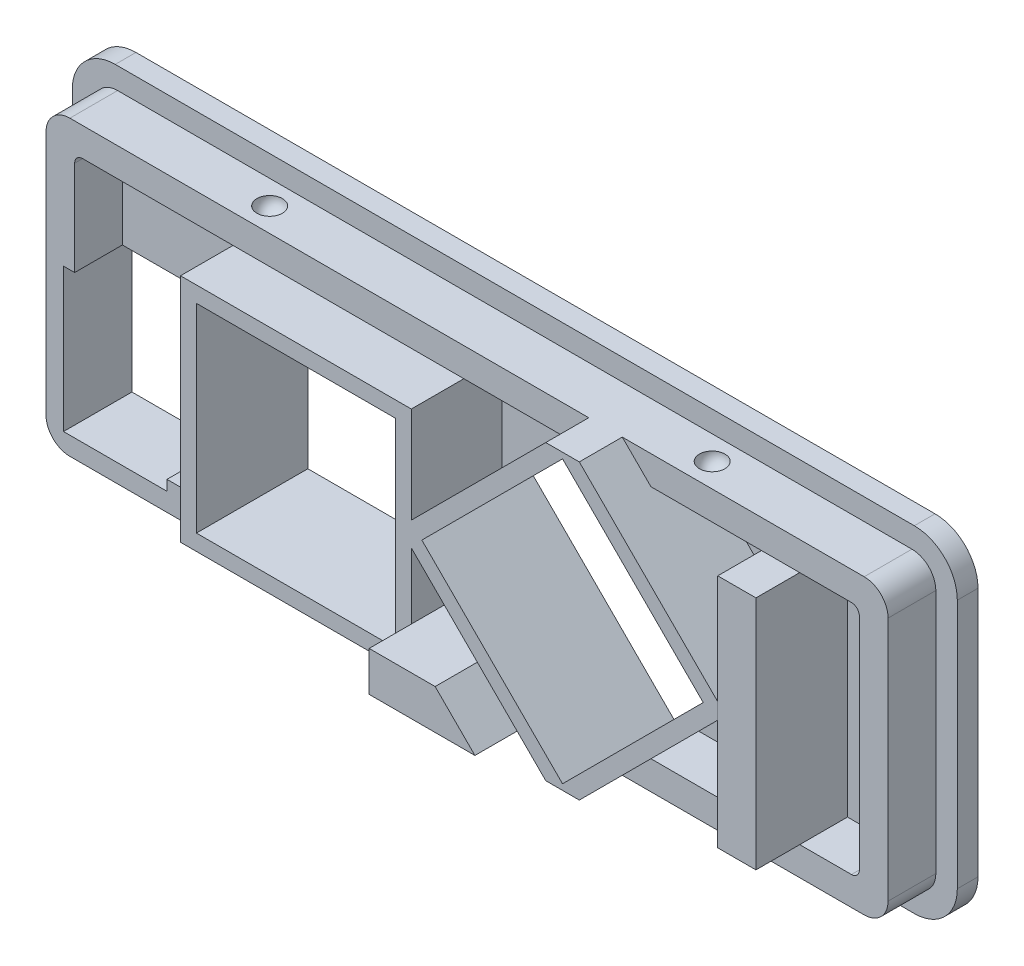
SolidWorks part; units mm, degrees
material "PLA"
ref_plane "Front Plane" through (0, 0, 0) normal (0, 0, 1) x (1, 0, 0)
ref_plane "Top Plane" through (0, 0, 0) normal (0, 1, 0) x (1, 0, 0)
ref_plane "Right Plane" through (0, 0, 0) normal (1, 0, 0) x (0, 0, -1)
sketch "Sketch1" plane through (0, 0, 0) normal (0, 0, 1) x (1, 0, 0)
  line L1 (2.7, 0) -> (52.9, 0)
  line L2 (0, 2.7) -> (0, 18.4)
  line L3 (2.7, 21.1) -> (52.9, 21.1)
  line L4 (55.6, 2.7) -> (55.6, 18.4)
  arc A0 (52.9, 0) -> (55.6, 2.7) centre (52.9, 2.7) ccw
  arc A1 (2.7, 0) -> (0, 2.7) centre (2.7, 2.7) cw
  arc A2 (0, 18.4) -> (2.7, 21.1) centre (2.7, 18.4) cw
  arc A3 (52.9, 21.1) -> (55.6, 18.4) centre (52.9, 18.4) cw
  point P9 (0, 0)
  dimension "D1" = 2.7
  dimension "D2" = 50.2
  dimension "D3" = 15.7
extrude "Boss-Extrude1" add sketch "Sketch1" along normal blind 1.3
sketch "Sketch4" plane through (0, 0, 1.3) normal (0, 0, 1) x (1, 0, 0)
  line L11 (54.25, 2.7) -> (54.25, 18.4)
  line L12 (52.9, 19.75) -> (2.7, 19.75)
  line L13 (1.35, 18.4) -> (1.35, 2.7)
  line L14 (2.7, 1.35) -> (52.9, 1.35)
  line L15 (54.25, 2.85) -> (54.25, 18.25)
  line L16 (52.75, 19.75) -> (2.85, 19.75)
  line L17 (1.35, 18.25) -> (1.35, 2.85)
  line L18 (2.85, 1.35) -> (52.75, 1.35)
  arc A4 (54.25, 18.25) -> (52.75, 19.75) centre (52.75, 18.25) ccw
  arc A5 (54.25, 2.85) -> (52.75, 1.35) centre (52.75, 2.85) cw
  arc A6 (1.35, 2.85) -> (2.85, 1.35) centre (2.85, 2.85) ccw
  arc A7 (2.85, 19.75) -> (1.35, 18.25) centre (2.85, 18.25) ccw
  arc A8 (52.9, 1.35) -> (54.25, 2.7) centre (52.9, 2.7) ccw
  arc A10 (54.25, 18.4) -> (52.9, 19.75) centre (52.9, 18.4) ccw
  arc A12 (2.7, 19.75) -> (1.35, 18.4) centre (2.7, 18.4) ccw
  arc A14 (1.35, 2.7) -> (2.7, 1.35) centre (2.7, 2.7) ccw
  dimension "D2" = 1.5
  dimension "D1" = 1.35
extrude "Boss-Extrude3" add sketch "Sketch4" along normal blind 3
sketch "Sketch5" plane through (0, 0, 4.3) normal (0, 0, 1) x (1, 0, 0)
  line L8 (52.45, 17.95) -> (3.15, 17.95)
  line L9 (3.15, 17.95) -> (3.15, 3.15)
  line L10 (3.15, 3.15) -> (52.45, 3.15)
  line L11 (52.45, 3.15) -> (52.45, 17.95)
  line L12 (51.95, 17.95) -> (3.65, 17.95)
  line L13 (3.15, 17.45) -> (3.15, 3.65)
  line L14 (3.65, 3.15) -> (51.95, 3.15)
  line L15 (52.45, 3.65) -> (52.45, 17.45)
  arc A4 (51.95, 3.15) -> (52.45, 3.65) centre (51.95, 3.65) ccw
  arc A5 (51.95, 17.95) -> (52.45, 17.45) centre (51.95, 17.45) cw
  arc A6 (3.65, 17.95) -> (3.15, 17.45) centre (3.65, 17.45) ccw
  arc A7 (3.15, 3.65) -> (3.65, 3.15) centre (3.65, 3.65) ccw
  dimension "D2" = 0.5
  dimension "D1" = 1.8
extrude "Cut-Extrude1" cut sketch "Sketch5" against normal blind 3
sketch "Sketch10" plane through (0, 19.75, 0) normal (0, 1, 0) x (1, 0, 0)
  line L0 (41.7, -2) -> (41.7, -3.6)
  line L1 (41.7, -3.6) -> (42.6713, -3.8888)
  line L3 (52.75, -1.3) -> (2.85, -1.3) construction
  line L4 (55.6, -1.3) -> (55.6, 0) construction
  arc A0 (41.7, -2) -> (41.7, -3.6) centre (41.7, -2.8) ccw
  dimension "D2" = 0.8
  dimension "D1" = 1.6
  dimension "D3" = 1.5
  dimension "D4" = 13.9
revolve "Cut-Revolve1" cut sketch "Sketch10" angle 360 about L0
ref_plane "Plane1" through (0, 10.55, 0) normal (0, -1, 0) x (-1, 0, 0)
mirror "Mirror1" about plane through (0, 10.55, 0) normal (0, -1, 0) of "Cut-Revolve1"
sketch "Sketch11" plane through (0, 0, 0) normal (0, 0, -1) x (-1, 0, 0)
  line L0 (0, 18.4) -> (0, 2.7) construction
  line L1 (-2.45, 2.5) -> (-8.95, 2.5)
  line L2 (-2.45, 2.5) -> (-2.45, 11.5)
  line L3 (-2.45, 11.5) -> (-8.95, 11.5)
  line L4 (-8.95, 2.5) -> (-8.95, 11.5)
  line L5 (-2.45, 2.5) -> (-8.95, 11.5) construction
  line L6 (-2.45, 11.5) -> (-8.95, 2.5) construction
  line L8 (-2.7, 0) -> (-52.9, 0) construction
  point P0 (-5.7, 7)
  dimension "D1" = 5.7
  dimension "D2" = 2.5
  dimension "D3" = 9
  dimension "D4" = 6.5
extrude "Cut-Extrude2" cut sketch "Sketch11" against normal blind 4.3
sketch "Sketch12" plane through (0, 0, 0) normal (0, 0, -1) x (-1, 0, 0)
  line L1 (-26, 16.35) -> (-13.5, 16.35)
  line L2 (-26, 16.35) -> (-26, 3.85)
  line L3 (-26, 3.85) -> (-13.5, 3.85)
  line L4 (-13.5, 16.35) -> (-13.5, 3.85)
  line L5 (-26, 16.35) -> (-13.5, 3.85) construction
  line L6 (-26, 3.85) -> (-13.5, 16.35) construction
  line L7 (-52.9, 21.1) -> (-2.7, 21.1) construction
  line L9 (0, 18.4) -> (0, 2.7) construction
  point P0 (-19.75, 10.1)
  dimension "D1" = 11
  dimension "D2" = 19.75
  dimension "D3" = 12.5
  dimension "D4" = 12.5
sketch "Sketch13" plane through (0, 0, 0) normal (0, 0, -1) x (-1, 0, 0)
  line L0 (-45.3388, 10.55) -> (-36.5, 1.7112)
  line L1 (-45.3388, 10.55) -> (-36.5, 19.3888)
  line L2 (-36.5, 1.7112) -> (-27.6612, 10.55)
  line L3 (-36.5, 19.3888) -> (-27.6612, 10.55)
  line L4 (-45.3388, 10.55) -> (-27.6612, 10.55) construction
  line L5 (-36.5, 1.7112) -> (-36.5, 19.3888) construction
  line L6 (-0.715, 10.55) -> (0.715, 10.55) construction
  line L7 (-52.9, 21.1) -> (-2.7, 21.1) construction
  line L10 (0, 18.4) -> (0, 2.7) construction
  point P1 (-36.5, 10.55)
  dimension "D1" = 0
  dimension "D2" = 10.55
  dimension "D3" = 12.5
  dimension "D5" = 36.5
extrude "Cut-Extrude4" cut sketch "Sketch12" against normal blind 1.3
sketch "Sketch17" plane through (0, 0, 0) normal (0, 0, -1) x (-1, 0, 0)
  line L8 (-13.5, 16.35) -> (-26, 16.35) construction
  line L9 (-27, 17.35) -> (-12.5, 17.35)
  line L10 (-27, 17.35) -> (-27, 2.85)
  line L11 (-27, 2.85) -> (-12.5, 2.85)
  line L12 (-12.5, 17.35) -> (-12.5, 2.85)
  line L13 (-26, 3.85) -> (-13.5, 3.85) construction
  line L14 (-13.5, 3.85) -> (-13.5, 16.35) construction
  line L15 (-26, 16.35) -> (-26, 3.85) construction
  line L17 (-13.5, 3.85) -> (-26, 3.85)
  line L18 (-13.5, 3.85) -> (-13.5, 16.35)
  line L19 (-13.5, 16.35) -> (-26, 16.35)
  line L20 (-26, 3.85) -> (-26, 16.35)
  dimension "D1" = 1
  dimension "D2" = 1
  dimension "D3" = 1
  dimension "D4" = 1
extrude "Boss-Extrude4" add sketch "Sketch17" against normal blind 7
extrude "Cut-Extrude5" cut sketch "Sketch13" against normal blind 4.3
sketch "Sketch18" plane through (0, 0, 0) normal (0, 0, -1) x (-1, 0, 0)
  line L18 (-36.5, 19.3888) -> (-45.3388, 10.55)
  line L19 (-45.3388, 10.55) -> (-36.5, 1.7112)
  line L20 (-36.5, 1.7112) -> (-27.6612, 10.55)
  line L21 (-27.6612, 10.55) -> (-36.5, 19.3888)
  line L22 (-46.753, 10.55) -> (-36.5, 0.297)
  line L23 (-36.5, 0.297) -> (-26.247, 10.55)
  line L24 (-26.247, 10.55) -> (-36.5, 20.803)
  line L25 (-36.5, 20.803) -> (-46.753, 10.55)
  line L26 (-46.753, 10.55) -> (-36.5, 0.297)
  line L27 (-36.5, 0.297) -> (-26.247, 10.55)
  line L28 (-26.247, 10.55) -> (-36.5, 20.803)
  line L29 (-36.5, 20.803) -> (-46.753, 10.55)
  dimension "D1" = 1
extrude "Boss-Extrude5" add sketch "Sketch18" against normal blind 7
sketch "Sketch20" plane through (0, 0, 4.3) normal (0, 0, 1) x (1, 0, 0)
  line L0 (35.447, 19.75) -> (37.553, 19.75)
  line L1 (35.447, 19.75) -> (2.85, 19.75) construction
  line L2 (52.75, 19.75) -> (37.553, 19.75) construction
  line L3 (37.553, 19.75) -> (36.5, 20.803)
  line L4 (36.5, 20.803) -> (35.447, 19.75)
extrude "Cut-Extrude6" cut sketch "Sketch20" against normal blind 3 and the other way blind 20
mirror "Mirror2" about plane through (0, 10.55, 0) normal (0, -1, 0) of "Cut-Extrude6"
sketch "Sketch21" plane through (0, 0, 0) normal (0, 0, -1) x (-1, 0, 0)
  line L0 (-52.9, 21.1) -> (-2.7, 21.1) construction
  line L1 (-30.25, 17.85) -> (-27.75, 17.85)
  line L2 (-30.25, 17.85) -> (-30.25, 15.35)
  line L3 (-30.25, 15.35) -> (-27.75, 15.35)
  line L4 (-27.75, 17.85) -> (-27.75, 15.35)
  line L5 (-30.25, 17.85) -> (-27.75, 15.35) construction
  line L6 (-30.25, 15.35) -> (-27.75, 17.85) construction
  line L7 (0, 18.4) -> (0, 2.7) construction
  point P0 (-29, 16.6)
  dimension "D1" = 4.5
  dimension "D2" = 2.5
  dimension "D3" = 2.5
  dimension "D4" = 29
extrude "Cut-Extrude7" cut sketch "Sketch21" against normal blind 10
ref_plane "Plane2" through (27.8, 0, 0) normal (-1, 0, 0) x (0, 0, 1)
mirror "Mirror3" about plane through (27.8, 0, 0) normal (-1, 0, 0) of "Mirror1", "Cut-Revolve1"
sketch "Sketch23" plane through (0, 0, 1.3) normal (0, 0, 1) x (1, 0, 0)
  line L0 (-0.715, 10.55) -> (0.715, 10.55) construction
  line L1 (48.7, 3.15) -> (46.3, 3.15)
  line L2 (48.7, 3.15) -> (48.7, 17.95)
  line L3 (48.7, 17.95) -> (46.3, 17.95)
  line L4 (46.3, 3.15) -> (46.3, 17.95)
  line L5 (48.7, 3.15) -> (46.3, 17.95) construction
  line L6 (48.7, 17.95) -> (46.3, 3.15) construction
  line L7 (39.353, 3.15) -> (51.95, 3.15) construction
  line L8 (51.95, 17.95) -> (39.353, 17.95) construction
  line L9 (0, 18.4) -> (0, 2.7) construction
  point P0 (47.5, 10.55)
  dimension "D1" = 2.4
  dimension "D2" = 47.5
extrude "Boss-Extrude6" add sketch "Sketch23" along normal blind 5.75
sketch "Sketch24" plane through (0, 0, 1.3) normal (0, 0, 1) x (1, 0, 0)
  line L0 (33.647, 3.15) -> (27, 3.15)
  line L2 (27, 3.15) -> (27, 5.65)
  line L4 (27, 5.65) -> (31.147, 5.65)
  line L5 (27, 9.797) -> (33.647, 3.15) construction
  line L6 (31.147, 5.65) -> (33.647, 3.15)
  line L7 (8.95, 3.15) -> (12.5, 3.15) construction
  line L8 (27, 11.303) -> (27, 17.35) construction
  dimension "D1" = 2.5
extrude "Boss-Extrude7" add sketch "Sketch24" along normal blind 8.35
equation "\"OutterLength\"= 55.6mm"
equation "\"OutterWidth\"= 21.1mm"
equation "\"EdgeRadius\"= 2.7mm"
equation "\"LipOffset\"= 1.35mm"
equation "\"LipHeight\"= 3mm"
equation "\"LipThickness\"= 1.8mm"
equation "\"LatchRadius\"= 0.8mm"
equation "\"D2@Sketch1\"=\"OutterLength\"-\"EdgeRadius\"*2"
equation "\"D3@Sketch1\"=\"OutterWidth\"-\"EdgeRadius\"*2"
equation "\"D1@Sketch1\"=\"EdgeRadius\""
equation "\"D1@Sketch4\"=\"LipOffset\""
equation "\"LipRadius\"= 1.5mm"
equation "\"D2@Sketch4\"=\"LipRadius\""
equation "\"D1@Sketch5\"=\"LipThickness\""
equation "\"D1@Boss-Extrude3\"=\"LipHeight\""
equation "\"D1@Cut-Extrude1\"=\"LipHeight\""
equation "\"D2@Sketch10\"=\"LatchRadius\""
equation "\"D1@Sketch10\"=\"LatchRadius\"*2"
equation "\"D3@Sketch10\"=\"LipHeight\"/2"
equation "\"D1@Cut-Extrude2\"=\"LipHeight\"+\"WallThickness\""
equation "\"WallThickness\"= 1.3mm"
equation "\"D1@Boss-Extrude1\"=\"WallThickness\""
equation "\"D1@Cut-Extrude4\"=\"WallThickness\""
equation "\"D1@Cut-Extrude5\"=\"WallThickness\"+\"LipHeight\""
equation "\"D1@Cut-Extrude6\"=\"LipHeight\""
equation "\"D2@Cut-Extrude6\"=20mm"
equation "\"D4@Sketch10\"=\"OutterLength\"/4"
equation "\"D2@Sketch13\"=\"OutterWidth\"/2"
